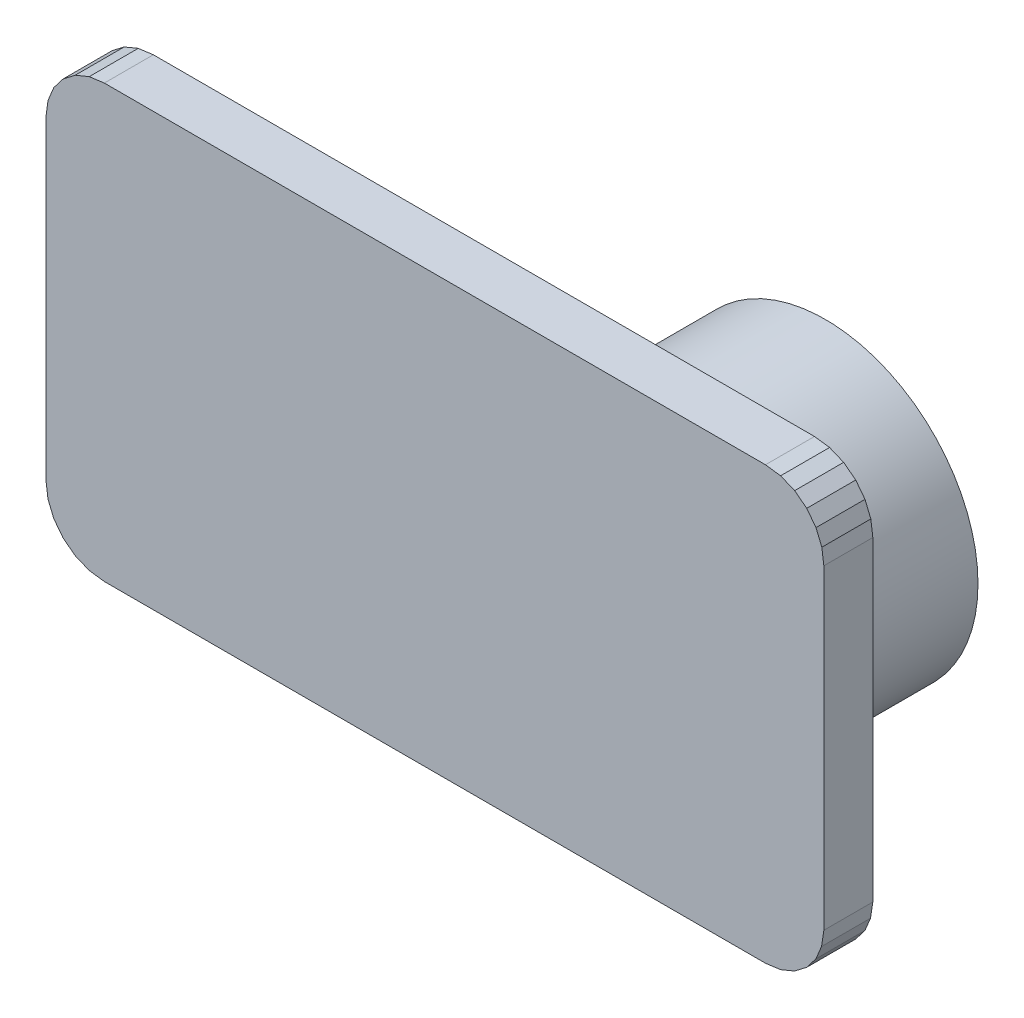
SolidWorks part; units mm, degrees
ref_plane "Front Plane" through (0, 0, 0) normal (0, 0, 1) x (1, 0, 0)
ref_plane "Top Plane" through (0, 0, 0) normal (0, 1, 0) x (1, 0, 0)
ref_plane "Right Plane" through (0, 0, 0) normal (1, 0, 0) x (0, 0, -1)
ref_plane "Dielectric_Layer Layer 1" through (0, 0, 1.6) normal (0, 0, 1) x (1, 0, 0)
sketch "Board_Outline" plane through (0, 0, 0) normal (0, 0, 1) x (1, 0, 0)
  line L0 (0, 12.192) -> (0, 1.905)
  line L1 (0, 1.905) -> (0.0649, 1.412)
  line L2 (0.0649, 1.412) -> (0.2552, 0.9525)
  line L3 (0.2552, 0.9525) -> (0.558, 0.558)
  line L4 (0.558, 0.558) -> (0.9525, 0.2552)
  line L5 (0.9525, 0.2552) -> (1.412, 0.0649)
  line L6 (1.412, 0.0649) -> (1.905, 0)
  line L7 (1.905, 0) -> (23.495, 0)
  line L8 (25.3258, 1.3895) -> (25.4, 1.8848)
  line L9 (25.142, 0.949) -> (25.3258, 1.3895)
  line L10 (25.142, 0.949) -> (24.842, 0.558)
  line L11 (24.842, 0.558) -> (24.4475, 0.2552)
  line L12 (24.4475, 0.2552) -> (23.9881, 0.0649)
  line L13 (23.495, 0) -> (23.9881, 0.0649)
  line L14 (25.4, 1.905) -> (25.4, 12.192)
  line L15 (25.4, 12.192) -> (25.3351, 12.6851)
  line L16 (25.3351, 12.6851) -> (25.1448, 13.1445)
  line L17 (25.1448, 13.1445) -> (24.842, 13.539)
  line L18 (24.842, 13.539) -> (24.4475, 13.8418)
  line L19 (24.4475, 13.8418) -> (23.9881, 14.0321)
  line L20 (23.9881, 14.0321) -> (23.495, 14.097)
  line L21 (23.495, 14.097) -> (1.905, 14.097)
  line L22 (1.905, 14.097) -> (1.412, 14.0321)
  line L23 (1.412, 14.0321) -> (0.9525, 13.8418)
  line L24 (0.9525, 13.8418) -> (0.558, 13.539)
  line L25 (0.558, 13.539) -> (0.2552, 13.1445)
  line L26 (0.2552, 13.1445) -> (0.0649, 12.6851)
  line L27 (0.0649, 12.6851) -> (0, 12.192)
  line L28 (25.4, 1.8848) -> (25.4, 1.905)
sketch "NPTH" plane through (0, 0, 0) normal (0, 0, 1) x (1, 0, 0)
  circle A0 centre (15.748, 4.445) radius 0.25
  circle A1 centre (7.493, 2.413) radius 0.25
  circle A2 centre (8.89, 10.541) radius 0.25
  circle A3 centre (13.97, 2.032) radius 0.25
  circle A4 centre (5.334, 4.064) radius 0.25
sketch "PTH" plane through (0, 0, 0) normal (0, 0, 1) x (1, 0, 0)
  circle A0 centre (1.4, 11.94) radius 0.5
  circle A1 centre (1.4, 9.4) radius 0.5
  circle A2 centre (1.4, 6.86) radius 0.5
  circle A3 centre (1.4, 4.32) radius 0.5
  circle A4 centre (1.4, 1.78) radius 0.5
  circle A5 centre (20.16, 8.41) radius 0.3
  circle A6 centre (20.16, 5.81) radius 0.3
  circle A7 centre (23.37, 12.07) radius 1.1
  circle A8 centre (23.37, 2.03) radius 1.1
extrude "Boss-Extrude1" add sketch "Board_Outline" along normal up to vertex (1.6 mm away)
sketch "Sketch1" plane through (0, 0, 0) normal (0, 0, -1) x (-1, 0, 0)
  circle A0 centre (-18.3498, 7.1012) radius 4.985
extrude "Boss-Extrude2" add sketch "Sketch1" along normal blind 5.5
